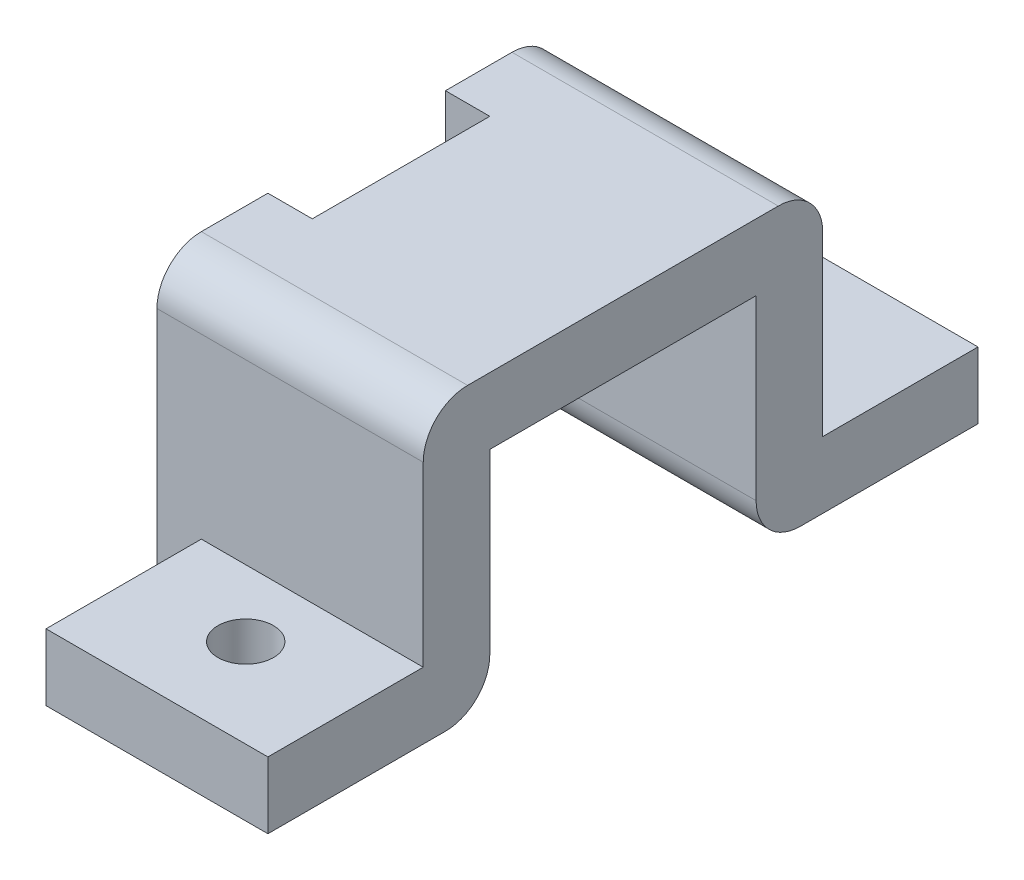
SolidWorks part; units mm, degrees
ref_plane "Front Plane" through (0, 0, 0) normal (0, 0, 1) x (1, 0, 0)
ref_plane "Top Plane" through (0, 0, 0) normal (0, 1, 0) x (1, 0, 0)
ref_plane "Right Plane" through (0, 0, 0) normal (1, 0, 0) x (0, 0, -1)
sketch "Sketch1" plane through (0, 0, 0) normal (1, 0, 0) x (0, 0, -1)
  line L0 (-9, 0) -> (9, 0)
  line L1 (9, 0) -> (9, -10)
  line L2 (9, -10) -> (16, -10)
  line L3 (16, -10) -> (16, -13)
  line L4 (16, -13) -> (6, -13)
  line L5 (6, -13) -> (6, -3)
  line L6 (6, -3) -> (-6, -3)
  line L7 (-6, -3) -> (-6, -13)
  line L8 (-6, -13) -> (-16, -13)
  line L9 (-16, -13) -> (-16, -10)
  line L12 (-9, 0) -> (-9, -10)
  line L13 (-9, -10) -> (-16, -10)
  point P13 (0, 0)
  point P14 (0, -3)
  dimension "D1" = 3
  dimension "D2" = 3
  dimension "D3" = 3
  dimension "D4" = 12
  dimension "D5" = 10
  dimension "D6" = 10
extrude "main" add sketch "Sketch1" along normal blind 10 contours L0 L1 L2 L3 L4 L5 L6 L7 L8 L9 L13 L12
fillet "Fillet1" radius 2 1 edges at (5, -13, 6)
fillet "Fillet2" radius 2 1 edges at (5, -13, -6)
sketch "Sketch2" plane through (0, -13, 0) normal (0, -1, 0) x (1, 0, 0)
  line L0 (0, 8) -> (0, 16) construction
  line L1 (0, -16) -> (0, -8) construction
  line L2 (10, -16) -> (0, -16) construction
  circle A0 centre (5, 12) radius 1.25
  circle A1 centre (5, -12) radius 1.25
  point P8 (0, 12)
  point P12 (0, -12)
  point P15 (5, -16)
  dimension "D1" = 2.5
extrude "bolt slot" cut sketch "Sketch2" against normal up to surface (3 mm away) up to face at (5, -10, -12.5)
sketch "Sketch3" plane through (0, 0, 0) normal (-1, 0, 0) x (0, 0, 1)
  line L0 (9, 0) -> (9, -10) construction
  line L6 (-9, -13) -> (-4, -13)
  line L7 (-9, -13) -> (-9, 0)
  line L8 (-9, 0) -> (-4, 0)
  line L9 (-4, -13) -> (-4, 0)
  line L10 (-6, -11) -> (-6, -3) construction
  line L11 (9, -13) -> (4, -13)
  line L12 (9, -13) -> (9, 0)
  line L13 (9, 0) -> (4, 0)
  line L14 (4, -13) -> (4, 0)
  line L16 (-16, -13) -> (-8, -13) construction
  point P0 (0, 0)
  dimension "D1" = 2
extrude "front tab" add sketch "Sketch3" along normal blind 2
sketch "Sketch4" plane through (0, -3, 0) normal (0, -1, 0) x (1, 0, 0)
  line L0 (10, -6) -> (0, -6) construction
  line L1 (8, -6) -> (6.5, -6)
  line L2 (8, -6) -> (8, -1)
  line L3 (8, -1) -> (6.5, -1)
  line L4 (6.5, -6) -> (6.5, -1)
  line L5 (10, -6) -> (10, 6) construction
  dimension "D1" = 2
  dimension "D2" = 1.5
  dimension "D3" = 5
extrude "top tab" add sketch "Sketch4" along normal blind 2
fillet "Fillet3" radius 2 1 edges at (4, 0, -9)
fillet "Fillet4" radius 2 1 edges at (4, 0, 9)
